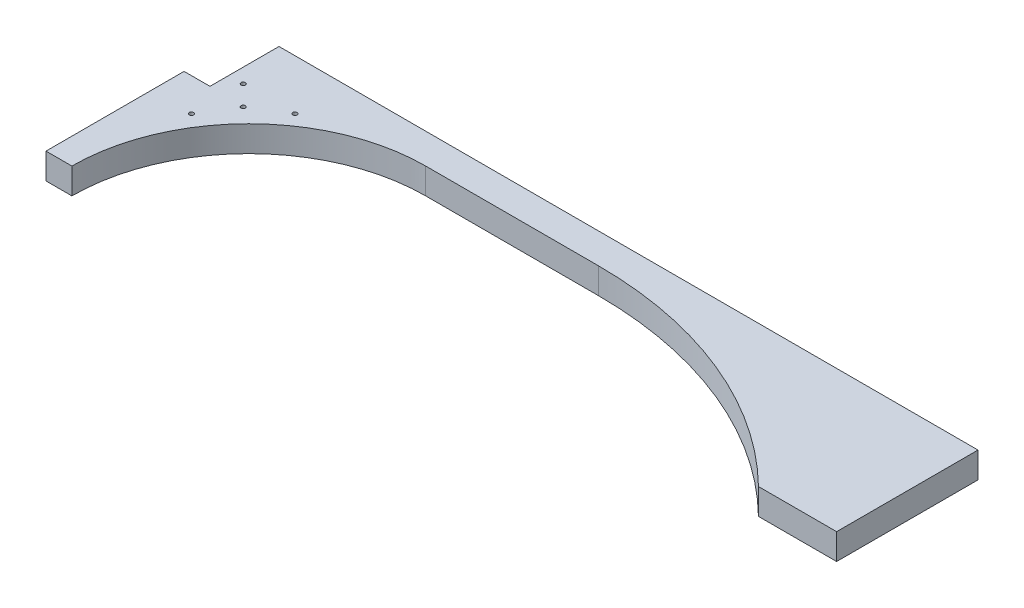
SolidWorks part; units mm, degrees
material "Pine"
ref_plane "Front Plane" through (0, 0, 0) normal (0, 0, 1) x (1, 0, 0)
ref_plane "Top Plane" through (0, 0, 0) normal (0, 1, 0) x (1, 0, 0)
ref_plane "Right Plane" through (0, 0, 0) normal (1, 0, 0) x (0, 0, -1)
sketch "Sketch1" plane through (0, 0, 0) normal (0, 1, 0) x (1, 0, 0)
  line L6 (-257.175, 0) -> (-257.175, -152.4) construction
  line L11 (-257.175, 0) -> (257.175, 0)
  line L13 (257.175, 0) -> (257.175, -104.0325)
  line L14 (0, -22.225) -> (0, 0) construction
  line L15 (0, -22.225) -> (257.175, -22.225) construction
  line L16 (0, -22.225) -> (-127, -22.225)
  line L17 (257.175, -104.0325) -> (199.6702, -104.0325)
  line L19 (-276.225, -50.8) -> (-276.225, -152.4)
  line L20 (-276.225, -152.4) -> (-257.175, -152.4)
  line L21 (-276.225, -50.8) -> (-257.175, -50.8)
  line L22 (-257.175, -50.8) -> (-257.175, 0)
  arc A5 (0, -22.225) -> (199.6702, -104.0325) centre (0, -306.7995) cw
  arc A6 (-127, -22.225) -> (-257.175, -152.4) centre (-127, -152.4) ccw
  point P2 (0, 0)
  dimension "D5" = 127
  dimension "D1" = 514.35
  dimension "D2" = 22.225
  dimension "D3" = 19.05
  dimension "D4" = 50.8
extrude "Boss-Extrude1" add sketch "Sketch1" along normal blind 19.05
hole_wizard "1/8 (0.125) Diameter Hole1" positions "Sketch2" profile "Sketch3" hole size "1/8" standard "ANSI Inch"
sketch "Sketch2" plane through (0, 0, 0) normal (0, -1, 0) x (-1, 0, 0)
  line L0 (212.725, -11.1125) -> (-238.125, -11.1125) construction
  line L1 (-238.125, -11.1125) -> (-238.125, -104.0325) construction
  line L3 (0, -22.225) -> (127, -22.225) construction
  line L4 (257.175, 0) -> (-257.175, 0) construction
  line L5 (-257.175, 0) -> (-257.175, -104.0325) construction
  line L6 (-212.725, -11.1125) -> (-238.125, -36.5125) construction
  line L9 (212.725, -11.1125) -> (238.125, -36.5125) construction
  line L12 (0, 0) -> (0, -22.225) construction
  line L13 (-257.175, -104.0325) -> (-199.6702, -104.0325) construction
  line L14 (-225.425, -23.8125) -> (-225.425, -67.52) construction
  line L15 (-225.425, -67.52) -> (-238.125, -67.52) construction
  line L16 (238.125, -36.5125) -> (257.175, -84.6006) construction
  line L18 (257.175, -84.6006) -> (238.125, -84.6006) construction
  line L19 (238.125, -84.6006) -> (238.125, -36.5125) construction
  line L21 (257.175, -84.6006) -> (276.225, -84.6006) construction
  line L22 (276.225, -50.8) -> (276.225, -152.4) construction
  arc A0 (257.175, -152.4) -> (127, -22.225) centre (127, -152.4) ccw construction
  point P4 (0, -11.1125)
  point P47 (225.425, -23.8125)
  point P49 (-225.425, -23.8125)
  point P57 (-225.425, -67.52)
  point P89 (257.175, -84.6006)
  dimension "D1" = 19.05
  dimension "D2" = 25.4
  dimension "D3" = 25.4
  dimension "D4" = 36.5125
sketch "Sketch3" plane through (0, 0, 11.1125) normal (1, 0, 0) x (0, 0, -1)
  line L0 (0, 0) -> (0, 12.0791)
  line L1 (0, 12.0791) -> (1.5875, 11.1252)
  line L2 (1.5875, 11.1252) -> (1.5875, 0)
  line L5 (1.5875, 0) -> (0, 0)
  line L10 (0, 12.0791) -> (-1.5875, 11.1252) construction
  line L11 (0, -6.35) -> (0, 107.95) construction
  dimension "Hole Dia." = 3.175
  dimension "Hole Depth" = 11.1252
  dimension "Drill Angle" = 118
sketch "Sketch4" plane through (0, 19.05, 0) normal (0, 1, 0) x (1, 0, 0)
  line L2 (-250.023, -108.2453) -> (-250.0259, -95.5464) construction
  line L3 (-256.3731, -108.2441) -> (-250.023, -108.2453) construction
  line L4 (-257.175, -50.8) -> (-257.175, 0) construction
  line L5 (-257.175, 0) -> (257.175, 0) construction
  line L13 (-205.579, -108.2531) -> (-199.236, -108.2543) construction
  line L18 (-256.3731, -108.2441) -> (-250.023, -108.2453) construction
  line L23 (-256.3555, -93.9209) -> (-256.3731, -108.2441) construction
  line L25 (-205.579, -108.2531) -> (-250.023, -108.2453) construction
  line L26 (-208.4525, -36.9612) -> (-246.5525, -36.9612) construction
  line L27 (-246.5525, -36.9612) -> (-246.5525, -75.0612) construction
  line L29 (-246.5525, -75.0612) -> (-208.4525, -75.0612) construction
  line L30 (-208.4525, -36.9612) -> (-208.4525, -75.0612) construction
  line L33 (-257.175, -50.8) -> (-257.175, -152.4) construction
  circle A2 centre (-208.4525, -36.9612) radius 3.9687
  circle A3 centre (-246.5525, -75.0612) radius 3.9687
  circle A4 centre (-246.5525, -36.9612) radius 3.9687
  arc A5 (-246.5525, -75.0612) -> (-208.4525, -36.9612) centre (-187.7362, -95.7776) cw construction
  ellipse E2 centre (-187.8402, -95.4653) end of major axis (-220.7714, -42.8574) minor radius 62.0454 (-173.0667, -35.1946) -> (-249.891, -95.462) ccw construction
  point P4 (-256.3731, -108.2441)
  point P5 (-256.3731, -108.2616)
  point P15 (-199.236, -108.2543)
  point P16 (-205.579, -108.2531)
  point P17 (-250.023, -108.2453)
  point P28 (0, 0)
  point P34 (-250.8915, -85.2186)
  point P41 (0, 0)
  point P45 (0, 0)
  point P46 (-256.3555, -93.9209)
  point P47 (0, 0)
  point P48 (-173.0591, -35.1928)
  point P57 (-231.83, -51.6838)
  dimension "D2" = 10.6225
  dimension "D1" = 7.9375
  dimension "D3" = 38.1
  dimension "D4" = 36.9612
hole_wizard "1/8 (0.125) Diameter Hole2" positions "Sketch5" profile "Sketch6" hole size "1/8" standard "ANSI Inch" end condition through all
sketch "Sketch5" plane through (0, 19.05, 0) normal (0, 1, 0) x (1, 0, 0)
  point P0 (-246.5525, -36.9612)
  point P3 (-208.4525, -36.9612)
  point P6 (-246.5525, -75.0612)
  point P10 (-231.83, -51.6838)
sketch "Sketch6" plane through (-246.5525, 19.05, 36.9612) normal (1, 0, 0) x (0, 0, 1)
  line L0 (0, 0) -> (0, 19.05)
  line L1 (0, 19.05) -> (1.5875, 19.05)
  line L2 (1.5875, 19.05) -> (1.5875, 0)
  line L5 (1.5875, 0) -> (0, 0)
  line L11 (0, -6.35) -> (0, 107.95) construction
  dimension "Thru Hole Dia." = 3.175
  dimension "Thru Hole Depth" = 19.05
